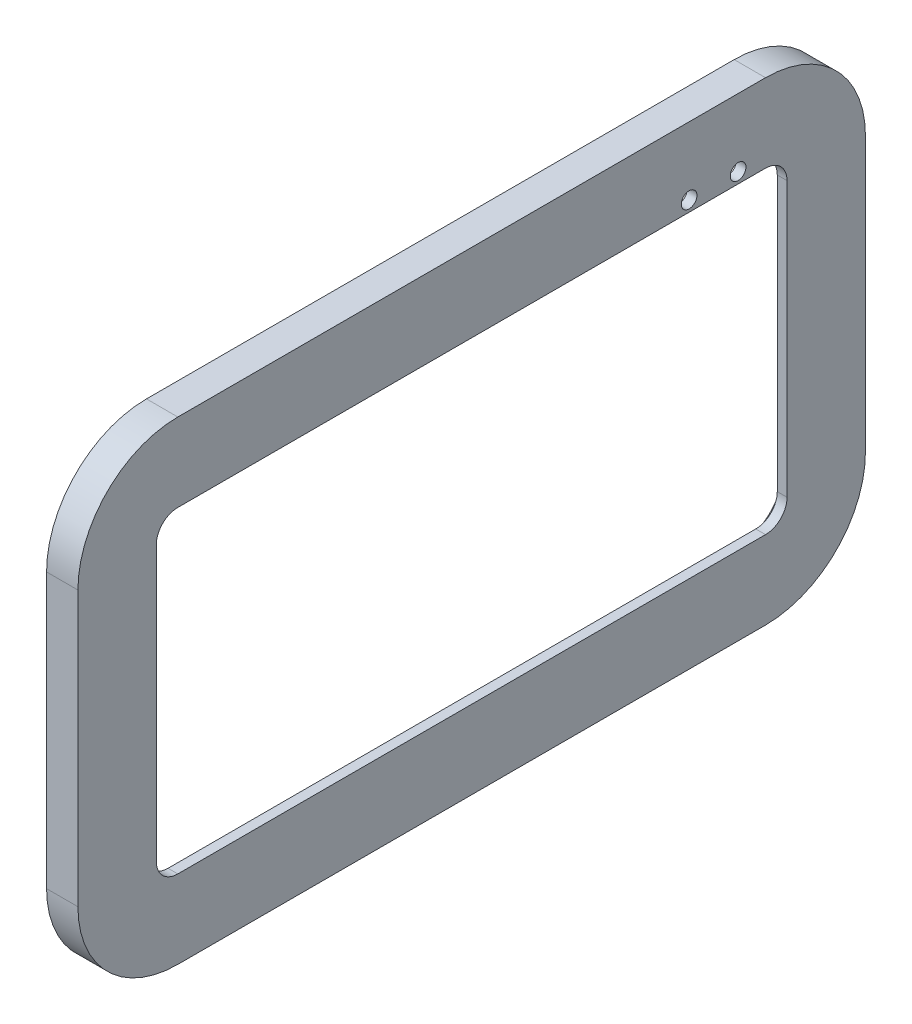
SolidWorks part; units mm, degrees
material "Ст 3 ГОСТ 380-88"
ref_plane "Front Plane" through (0, 0, 0) normal (0, 0, 1) x (1, 0, 0)
ref_plane "Top Plane" through (0, 0, 0) normal (0, 1, 0) x (1, 0, 0)
ref_plane "Right Plane" through (0, 0, 0) normal (1, 0, 0) x (0, 0, -1)
sketch "Sketch1" plane through (0, 0, 0) normal (0, 0, 1) x (1, 0, 0)
  line L1 (-3, 96) -> (-3, 121)
  line L2 (8, 96) -> (-3, 96) construction
  line L3 (8, 96) -> (-3, 96)
  line L4 (8, 81) -> (8, 96) construction
  line L5 (8, 81) -> (8, 96)
  line L6 (-3, 121) -> (13, 121)
  line L7 (13, 121) -> (13, 81)
  line L8 (13, 81) -> (8, 81)
  dimension "D1" = 5
sketch "Sketch2" plane through (0, 0, 0) normal (1, 0, 0) x (0, 0, -1)
  line L4 (150, 92) -> (-150, 92)
  line L5 (-172, 70) -> (-172, -70)
  line L6 (-150, -92) -> (150, -92)
  line L7 (172, -70) -> (172, 70)
  line L8 (150, 92) -> (-150, 92)
  line L9 (-172, 70) -> (-172, -70)
  line L10 (-150, -92) -> (150, -92)
  line L11 (172, -70) -> (172, 70)
  arc A4 (-150, 92) -> (-172, 70) centre (-150, 70) ccw
  arc A5 (-172, -70) -> (-150, -92) centre (-150, -70) ccw
  arc A6 (150, -92) -> (172, -70) centre (150, -70) ccw
  arc A7 (172, 70) -> (150, 92) centre (150, 70) ccw
  arc A8 (-150, 92) -> (-172, 70) centre (-150, 70) ccw
  arc A9 (-172, -70) -> (-150, -92) centre (-150, -70) ccw
  arc A10 (150, -92) -> (172, -70) centre (150, -70) ccw
  arc A11 (172, 70) -> (150, 92) centre (150, 70) ccw
  dimension "D1" = 0
sweep "Sweep1" add profiles "Sketch1" path "Sketch2"
sketch "Sketch5" plane through (13, 0, 0) normal (1, 0, 0) x (0, 0, -1)
  line L0 (201, 70) -> (201, -70) construction
  line L1 (-150, 121) -> (0, 121) construction
  line L2 (-201, -70) -> (-201, 70) construction
  line L3 (150, -121) -> (-150, -121) construction
  line L4 (201, 70) -> (201, -70)
  line L5 (-150, 121) -> (150, 121)
  line L6 (-201, -70) -> (-201, 70)
  line L7 (150, -121) -> (-150, -121)
  line L9 (-161, -70) -> (-161, 70) construction
  line L10 (150, -81) -> (-150, -81) construction
  line L11 (161, 70) -> (161, -70) construction
  line L12 (0, 81) -> (150, 81) construction
  line L14 (-161, -70) -> (-161, 70)
  line L15 (150, -81) -> (-150, -81)
  line L16 (161, 70) -> (161, -70)
  line L17 (-150, 81) -> (150, 81)
  arc A0 (201, 70) -> (150, 121) centre (150, 70) ccw construction
  arc A1 (-150, 121) -> (-201, 70) centre (-150, 70) ccw construction
  arc A2 (150, -121) -> (201, -70) centre (150, -70) ccw construction
  arc A3 (-201, -70) -> (-150, -121) centre (-150, -70) ccw construction
  arc A4 (201, 70) -> (150, 121) centre (150, 70) ccw
  arc A5 (-150, 121) -> (-201, 70) centre (-150, 70) ccw
  arc A6 (150, -121) -> (201, -70) centre (150, -70) ccw
  arc A7 (-201, -70) -> (-150, -121) centre (-150, -70) ccw
  arc A8 (-150, 81) -> (-161, 70) centre (-150, 70) ccw construction
  arc A9 (-161, -70) -> (-150, -81) centre (-150, -70) ccw construction
  arc A10 (150, -81) -> (161, -70) centre (150, -70) ccw construction
  arc A11 (161, 70) -> (150, 81) centre (150, 70) ccw construction
  arc A12 (-150, 81) -> (-161, 70) centre (-150, 70) ccw
  arc A13 (-161, -70) -> (-150, -81) centre (-150, -70) ccw
  arc A14 (150, -81) -> (161, -70) centre (150, -70) ccw
  arc A15 (161, 70) -> (150, 81) centre (150, 70) ccw
extrude "Boss-Extrude1" add sketch "Sketch5" against normal up to surface (16 mm away) up to face at (-3, -93.2368, 173.2368)
sketch "Sketch6" plane through (-3, 0, 0) normal (-1, 0, 0) x (0, 0, 1)
  line L24 (176, -70) -> (176, 70)
  line L25 (-150, -96) -> (150, -96)
  line L26 (-176, 70) -> (-176, -70)
  line L27 (150, 96) -> (-150, 96)
  line L28 (176, -70) -> (176, 70)
  line L29 (-150, -96) -> (150, -96)
  line L30 (-176, 70) -> (-176, -70)
  line L31 (150, 96) -> (-150, 96)
  arc A20 (176, 70) -> (150, 96) centre (150, 70) ccw
  arc A21 (150, -96) -> (176, -70) centre (150, -70) ccw
  arc A22 (-176, -70) -> (-150, -96) centre (-150, -70) ccw
  arc A23 (-150, 96) -> (-176, 70) centre (-150, 70) ccw
  arc A24 (176, 70) -> (150, 96) centre (150, 70) ccw
  arc A25 (150, -96) -> (176, -70) centre (150, -70) ccw
  arc A26 (-176, -70) -> (-150, -96) centre (-150, -70) ccw
  arc A27 (-150, 96) -> (-176, 70) centre (-150, 70) ccw
  dimension "D1" = 15
extrude "Cut-Extrude3" cut sketch "Sketch6" against normal blind 11
sketch "Sketch3" plane through (13, 0, 0) normal (1, 0, 0) x (0, 0, -1)
  line L0 (111, 86.5) -> (136, 86.5) construction
  line L1 (-150, 81) -> (150, 81) construction
  line L3 (111, 92) -> (111, 81) construction
  line L4 (136, 92) -> (136, 81) construction
  line L5 (172, -70) -> (172, 70) construction
  line L9 (0, 92) -> (150, 92) construction
  circle A0 centre (111, 86.5) radius 4
  circle A1 centre (136, 86.5) radius 4
  dimension "D2" = 8
  dimension "D1" = 25
  dimension "D3" = 36
extrude "Cut-Extrude1" cut sketch "Sketch3" against normal through all
sketch "Sketch4" plane through (-3, 0, 0) normal (-1, 0, 0) x (0, 0, 1)
  circle A7 centre (-188.5, 0) radius 4
  circle A8 centre (-188.5, 0) radius 4
  circle A11 centre (188.5, 0) radius 4
  circle A12 centre (188.5, 0) radius 4
  dimension "D4" = 0
  dimension "D6" = 0
hole_wizard "Ø8.0mm Dowel Hole1" positions "3DSketch1" profile "Sketch7" hole size "Ø8.0" standard "ANSI Metric"
sketch3d "3DSketch1"
  point P0 (-3, 0, -188.5)
  point P3 (-3, 0, 188.5)
sketch "Sketch7" plane through (-3, 0, -188.5) normal (0, 1, 0) x (0, 0, 1)
  line L0 (0, 0) -> (0, 14.4034)
  line L1 (0, 14.4034) -> (4, 12)
  line L2 (4, 12) -> (4, 0)
  line L5 (4, 0) -> (0, 0)
  line L10 (0, 14.4034) -> (-4, 12) construction
  line L11 (0, -6.35) -> (0, 107.95) construction
  dimension "Hole Dia." = 8
  dimension "Hole Depth" = 12
  dimension "Drill Angle" = 118
